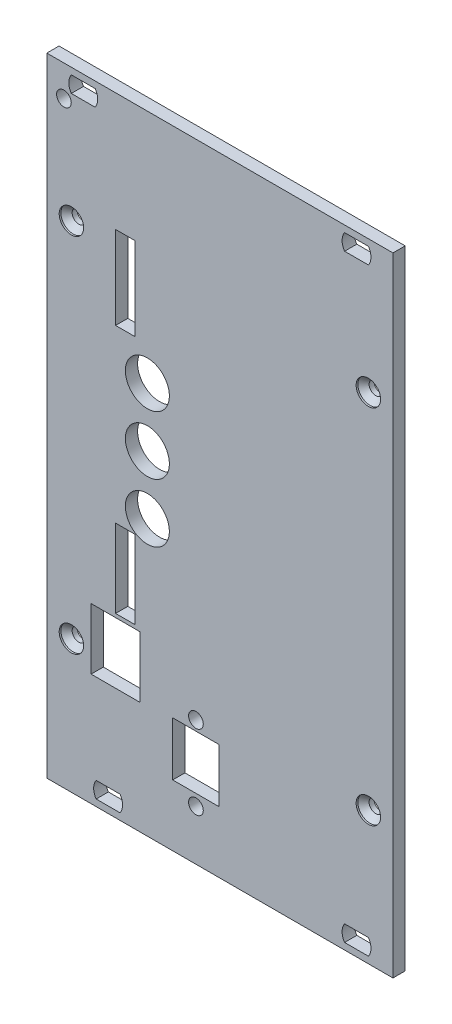
SolidWorks part; units mm, degrees
ref_plane "Front Plane" through (0, 0, 0) normal (0, 0, 1) x (1, 0, 0)
ref_plane "Top Plane" through (0, 0, 0) normal (0, 1, 0) x (1, 0, 0)
ref_plane "Right Plane" through (0, 0, 0) normal (1, 0, 0) x (0, 0, -1)
ref_plane "Plane1" through (0, 0, 2.5) normal (0, 0, 1) x (1, 0, 0)
sketch "Sketch1" plane through (0, 0, 2.5) normal (0, 0, 1) x (1, 0, 0)
  line L0 (63.33, 125.4) -> (-7.45, 125.4)
  line L1 (-7.45, 125.4) -> (-7.45, -3)
  line L2 (-7.45, -3) -> (63.33, -3)
  line L3 (63.33, -3) -> (63.33, 125.4)
  dimension "D1" = 70.78
  dimension "D2" = 128.4
extrude "Bulk" add sketch "Sketch1" against normal blind 2.5
sketch "Sketch2" plane through (0, 0, 2.5) normal (0, 0, 1) x (1, 0, 0)
  line L0 (2.4454, 124.05) -> (-2.4454, 124.05)
  line L1 (-2.4454, 120.75) -> (2.4454, 120.75)
  arc A0 (-2.4454, 124.05) -> (-2.4454, 120.75) centre (0, 122.4) ccw
  arc A1 (2.4454, 120.75) -> (2.4454, 124.05) centre (0, 122.4) ccw
extrude "Mount hole NW" cut sketch "Sketch2" against normal through all
pattern_linear "Mount holes NE SE" count 2 spacing 55.88 along (1, 0, 0) count 2 spacing 122.4 along (0, -1, 0) skipping (0, 1) of "Mount hole NW"
sketch "Sketch4" plane through (0, 0, 0) normal (0, 0, -1) x (-1, 0, 0)
  line L0 (3.82, 15.8) -> (-0.08, 15.8)
  line L1 (-0.08, 15.8) -> (-0.08, 1.2)
  line L2 (-0.08, 1.2) -> (3.82, 1.2)
  line L3 (3.82, 1.2) -> (3.82, 15.8)
  line L4 (7.45, 125.4) -> (7.45, -3) construction
  dimension "D1" = 3.63
extrude "Handle hole" [suppressed] cut sketch "Sketch4" against normal through all
sketch "Sketch3" plane through (0, 0, 2.5) normal (0, 0, 1) x (1, 0, 0)
  line L0 (7.5254, 1.65) -> (2.6346, 1.65)
  line L1 (2.6346, -1.65) -> (7.5254, -1.65)
  arc A0 (2.6346, 1.65) -> (2.6346, -1.65) centre (5.08, 0) ccw
  arc A1 (7.5254, -1.65) -> (7.5254, 1.65) centre (5.08, 0) ccw
extrude "Mount hole SW" cut sketch "Sketch3" against normal through all
hole_wizard "Alignment hole" positions "Sketch6" profile "Sketch5" hole size "Ø3.0" standard "ANSI Metric"
sketch "Sketch6" plane through (0, 0, 2.5) normal (0, 0, 1) x (1, 0, 0)
  point P0 (-3.95, 119.1)
sketch "Sketch5" plane through (-3.95, 119.1, 2.5) normal (1, 0, 0) x (0, -1, 0)
  line L0 (0, 0) -> (0, 2.5)
  line L1 (0, 2.5) -> (1.5, 2.5)
  line L2 (1.5, 2.5) -> (1.5, 0)
  line L5 (1.5, 0) -> (0, 0)
  line L11 (0, -6.35) -> (0, 107.95) construction
  dimension "Thru Hole Dia." = 3
  dimension "Thru Hole Depth" = 2.5
hole_wizard "Drill holes" positions "Sketch8" profile "Sketch7" countersink size "M2.5" standard "ANSI Metric" end condition through all
sketch "Sketch8" plane through (0, 0, 2.5) normal (0, 0, 1) x (1, 0, 0)
  line L0 (-7.45, -3) -> (63.33, -3) construction
  line L2 (-7.45, 125.4) -> (-7.45, -3) construction
  point P0 (-2.42, 24.2)
  point P1 (-2.42, 98.2)
  point P22 (58.3, 98.2)
  point P27 (58.3, 24.2)
  dimension "D1" = 27.2
  dimension "D2" = 5.03
  dimension "D3" = 5.03
  dimension "D4" = 101.2
  dimension "D5" = 2
  dimension "D6" = 2
sketch "Sketch7" plane through (-2.42, 24.2, 2.5) normal (1, 0, 0) x (0, -1, 0)
  line L0 (0, 0) -> (0, 2.5)
  line L1 (0, 2.5) -> (1.35, 2.5)
  line L2 (1.35, 2.5) -> (1.35, 1.5)
  line L3 (1.35, 1.5) -> (2.5, 0.35)
  line L4 (2.5, 0.35) -> (2.5, 0)
  line L6 (2.5, 0) -> (0, 0)
  line L7 (-1.35, 1.5) -> (-2.5, 0.35) construction
  line L11 (0, -6.35) -> (0, 107.95) construction
  dimension "Thru Hole Dia." = 2.7
  dimension "Thru Hole Depth" = 2.5
  dimension "C'Sink Dia." = 5
  dimension "C'Sink Angle" = 90
  dimension "Head Clearance" = 0.35
ref_plane "Board bottom" through (0, 11.2, 0) normal (0, -1, 0) x (-1, 0, 0)
ref_plane "Board top" through (0, 111.2, 0) normal (0, 1, 0) x (1, 0, 0)
ref_plane "Board upper surface" through (6.61, 0, 0) normal (-1, 0, 0) x (0, 0, 1)
ref_plane "Board lower surface" through (5.01, 0, 0) normal (-1, 0, 0) x (0, 0, 1)
sketch "Sketch9" plane through (0, 0, 2.5) normal (0, 0, 1) x (1, 0, 0)
  line L1 (11.61, 32.45) -> (1.61, 32.45)
  line L2 (1.61, 19.95) -> (11.61, 19.95)
  line L3 (11.61, 19.95) -> (11.61, 32.45)
  line L4 (6.61, 1.375) -> (6.61, -1.375) construction
  line L5 (-28.8918, 11.2) -> (28.8918, 11.2) construction
  line L6 (1.7, 32.45) -> (1.7, 19.95) construction
  line L9 (1.61, 32.45) -> (1.61, 19.95)
  line L10 (1.61, 32.45) -> (11.61, 19.95) construction
  line L11 (11.61, 32.45) -> (1.61, 19.95) construction
  point P8 (6.61, 26.2)
  dimension "D1" = 10
  dimension "D5" = 15
  dimension "D7" = 12.5
extrude "USB" cut sketch "Sketch9" against normal through all
sketch "Sketch10" plane through (0, 0, 2.5) normal (0, 0, 1) x (1, 0, 0)
  line L1 (6.61, 37.2) -> (10.61, 37.2) construction
  line L2 (6.61, 37.2) -> (6.61, 33.2)
  line L3 (6.61, 33.2) -> (10.61, 33.2)
  line L4 (10.61, 37.2) -> (10.61, 33.2)
  line L5 (6.61, 37.2) -> (10.61, 33.2) construction
  line L6 (6.61, 33.2) -> (10.61, 37.2) construction
  line L7 (6.61, 1.375) -> (6.61, -1.375) construction
  line L8 (8.61, 35.2) -> (10.61, 35.2) construction
  line L9 (-28.8918, 11.2) -> (28.8918, 11.2) construction
  line L10 (10.61, 33.2) -> (6.61, 33.2)
  line L11 (10.61, 33.2) -> (10.61, 49.2)
  line L12 (10.61, 49.2) -> (6.61, 49.2)
  line L13 (6.61, 33.2) -> (6.61, 49.2)
  point P0 (8.61, 35.2)
  point P13 (8.61, 33.2)
  dimension "D1" = 4
  dimension "D2" = 4
  dimension "D3" = 24
  dimension "D4" = 0
  dimension "D5" = 16
extrude "MCXX" cut sketch "Sketch10" against normal through all contours L13 L2 L3 L4 L11 L12
sketch "Sketch12" plane through (0, 0, 2.5) normal (0, 0, 1) x (1, 0, 0)
  line L0 (6.61, 1.375) -> (6.61, -1.375) construction
  line L1 (-28.8918, 11.2) -> (28.8918, 11.2) construction
  circle A0 centre (13.11, 53.2) radius 4.5
  dimension "D1" = 9
  dimension "D2" = 6.5
  dimension "D3" = 42
extrude "Selector 1" cut sketch "Sketch12" against normal through all
pattern_linear "Copy selector" count 3 spacing 12 along (0, 1, 0) of "Selector 1"
sketch "Sketch27" plane through (0, 0, 2.5) normal (0, 0, 1) x (1, 0, 0)
  line L0 (6.61, 88.2) -> (10.61, 88.2) construction
  line L1 (6.61, 88.2) -> (6.61, 84.2)
  line L2 (6.61, 84.2) -> (10.61, 84.2)
  line L3 (10.61, 88.2) -> (10.61, 84.2)
  line L4 (6.61, 88.2) -> (10.61, 84.2) construction
  line L5 (6.61, 84.2) -> (10.61, 88.2) construction
  line L6 (8.61, 86.2) -> (10.61, 86.2) construction
  line L7 (10.61, 84.2) -> (6.61, 84.2)
  line L8 (10.61, 84.2) -> (10.61, 101.2)
  line L9 (10.61, 101.2) -> (6.61, 101.2)
  line L10 (6.61, 84.2) -> (6.61, 101.2)
  line L11 (6.61, 1.375) -> (6.61, -1.375) construction
  line L12 (-28.8918, 11.2) -> (28.8918, 11.2) construction
  point P0 (8.61, 86.2)
  point P9 (8.61, 101.2)
  dimension "D1" = 4
  dimension "D2" = 4
  dimension "D3" = 90
  dimension "D4" = 75
extrude "MMCX 2" cut sketch "Sketch27" against normal through all contours L10 L1 L2 L3 L8 L9
sketch "Sketch25" plane through (0, 0, 2.5) normal (0, 0, 1) x (1, 0, 0)
  line L0 (23.0439, 46.1205) -> (23.0439, 35.6205) construction
  line L1 (18.2939, 20.5574) -> (27.7939, 20.5574)
  line L2 (18.2939, 20.5574) -> (18.2939, 9.5574)
  line L3 (18.2939, 9.5574) -> (27.7939, 9.5574)
  line L4 (27.7939, 20.5574) -> (27.7939, 9.5574)
  circle A2 centre (23.0439, 22.5574) radius 1.5
  circle A3 centre (23.0439, 7.2574) radius 1.5
  dimension "D5" = 3
  dimension "D6" = 3
  dimension "D1" = 11
  dimension "D2" = 9.5
  dimension "D3" = 15.3
  dimension "D4" = 13
extrude "Barrel Jack" cut sketch "Sketch25" against normal through all
sketch "Sketch13" plane through (0, 0, 2.5) normal (0, 0, 1) x (1, 0, 0)
  line L3 (6.61, 1.375) -> (6.61, -1.375) construction
  text T0 "TTL"
  dimension "D1" = 6.2
extrude "Text TTL" [suppressed] cut sketch "Sketch13" against normal blind 0.5
sketch "Sketch14" [suppressed] plane through (0, 0, 2.5) normal (0, 0, 1) x (1, 0, 0)
  line L0 (2.4249, 90.2) -> (2.4249, 103.4646) construction
  line L8 (2.4249, 99.341) -> (2.4249, 99.7) construction
  text T0 "S-T"
extrude "Text ST" [suppressed] cut sketch "Sketch14" against normal blind 0.5
sketch "Sketch15" [suppressed] plane through (0, 0, 2.5) normal (0, 0, 1) x (1, 0, 0)
  line L2 (2.5146, 100.8615) -> (2.5146, 78.0624) construction
  text T0 "Sine"
extrude "Text Sine" [suppressed] cut sketch "Sketch15" against normal blind 0.5
ref_plane "Text align 2" [suppressed] through (38.33, 0, 0) normal (1, 0, 0) x (0, 0, -1)
sketch "Sketch17" [suppressed] plane through (0, 0, 2.5) normal (0, 0, 1) x (1, 0, 0)
  line L1 (2.68, 69.7) -> (38.33, 69.7) construction
  line L2 (38.33, -1.375) -> (38.33, 1.375) construction
  line L3 (38.33, 69.7) -> (38.33, 59.5505) construction
  circle A0 centre (2.68, 65.2) radius 4.5 construction
  text T0 "Stop1" font "Century Gothic" height 2
extrude "Cut-Extrude11" [suppressed] cut sketch "Sketch17" against normal blind 0.5
sketch "Sketch18" [suppressed] plane through (0, 0, 2.5) normal (0, 0, 1) x (1, 0, 0)
  line L0 (2.68, 57.7) -> (38.33, 57.7) construction
  line L1 (38.33, -1.375) -> (38.33, 1.375) construction
  line L2 (38.33, 57.7) -> (38.33, 47.8465) construction
  circle A0 centre (2.68, 53.2) radius 4.5 construction
  text T0 "Start" font "Century Gothic" height 2
extrude "Cut-Extrude12" [suppressed] cut sketch "Sketch18" against normal blind 0.5
sketch "Sketch21" [suppressed] plane through (0, 0, 2.5) normal (0, 0, 1) x (1, 0, 0)
  line L0 (2.68, 81.7) -> (38.33, 81.7) construction
  line L1 (38.33, -1.375) -> (38.33, 1.375) construction
  line L2 (38.33, 81.7) -> (38.33, 70.7585) construction
  circle A0 centre (2.68, 77.2) radius 4.5 construction
  text T0 "Stop2" font "Century Gothic" height 2
extrude "Cut-Extrude14" [suppressed] cut sketch "Sketch21" against normal blind 0.5
sketch "Sketch23" plane through (0, 0, 2.5) normal (0, 0, 1) x (1, 0, 0)
  line L0 (12.61, 49.2) -> (12.61, 33.2) construction
  line L1 (10.61, 33.2) -> (10.61, 49.2) construction
  line L5 (10.61, 49.2) -> (10.61, 33.2) construction
  text T0 "TTL Buffers" font "Century Gothic" height 2
  dimension "D1" = 2
extrude "Cut-Extrude15" [suppressed] cut sketch "Sketch23" against normal blind 0.5
sketch "Sketch24" [suppressed] plane through (0, 0, 2.5) normal (0, 0, 1) x (1, 0, 0)
  line L0 (38.33, 49.2) -> (38.33, 15.9676) construction
  line L1 (38.33, -1.375) -> (38.33, 1.375) construction
  text T0 "RF Correlation"
extrude "Main title" [suppressed] cut sketch "Sketch24" against normal blind 0.5
